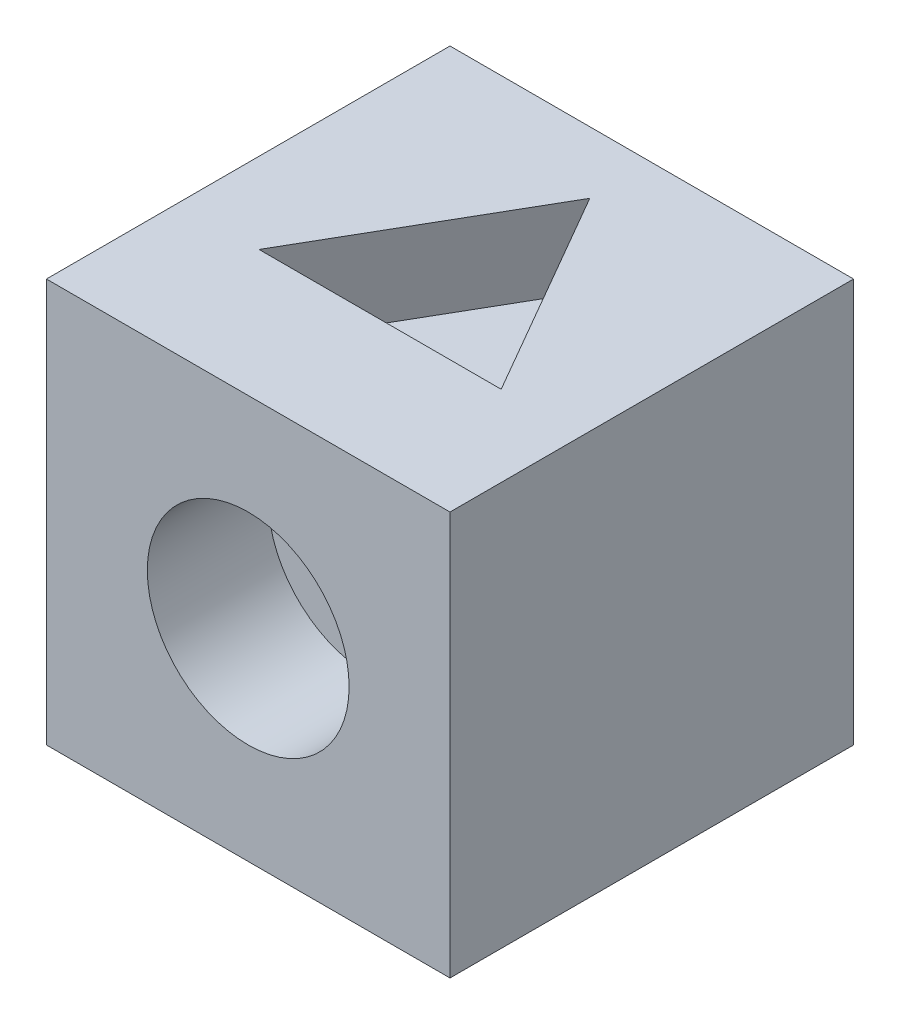
SolidWorks part; units mm, degrees
material "AISI 1020"
ref_plane "Front Plane" through (0, 0, 0) normal (0, 0, 1) x (1, 0, 0)
ref_plane "Top Plane" through (0, 0, 0) normal (0, 1, 0) x (1, 0, 0)
ref_plane "Right Plane" through (0, 0, 0) normal (1, 0, 0) x (0, 0, -1)
sketch "Sketch1" plane through (0, 0, 0) normal (0, 1, 0) x (1, 0, 0)
  line L1 (-50, -50) -> (50, -50)
  line L2 (-50, -50) -> (-50, 50)
  line L3 (-50, 50) -> (50, 50)
  line L4 (50, -50) -> (50, 50)
  line L5 (-50, -50) -> (50, 50) construction
  line L6 (-50, 50) -> (50, -50) construction
  point P0 (0, 0)
  dimension "D1" = 100
  dimension "D2" = 100
extrude "Boss-Extrude1" add sketch "Sketch1" along normal blind 100
sketch "Sketch2" plane through (0, 0, 50) normal (0, 0, 1) x (1, 0, 0)
  line L0 (0, 0) -> (0, 100) construction
  line L1 (-50, 100) -> (50, 100) construction
  circle A0 centre (0, 50) radius 25
  dimension "D1" = 50
extrude "Cut-Extrude1" cut sketch "Sketch2" against normal blind 30
sketch "Sketch3" plane through (0, 100, 0) normal (0, 1, 0) x (1, 0, 0)
  line L1 (0, 34.641) -> (-30, -17.3205)
  line L2 (-30, -17.3205) -> (30, -17.3205)
  line L3 (30, -17.3205) -> (0, 34.641)
  circle A0 centre (0, 0) radius 17.3205 construction
  dimension "D1" = 60
extrude "Cut-Extrude2" cut sketch "Sketch3" against normal blind 20
equation "\"A\"= 100"
equation "\"B\"= 100"
equation "\"C\"= 100"
equation "\"D\"= 100"
equation "\"E\"= 100"
equation "\"D1@Sketch1\"=\"A\""
equation "\"D2@Sketch1\"=\"B\""
equation "\"D1@Boss-Extrude1\"=\"C\""
